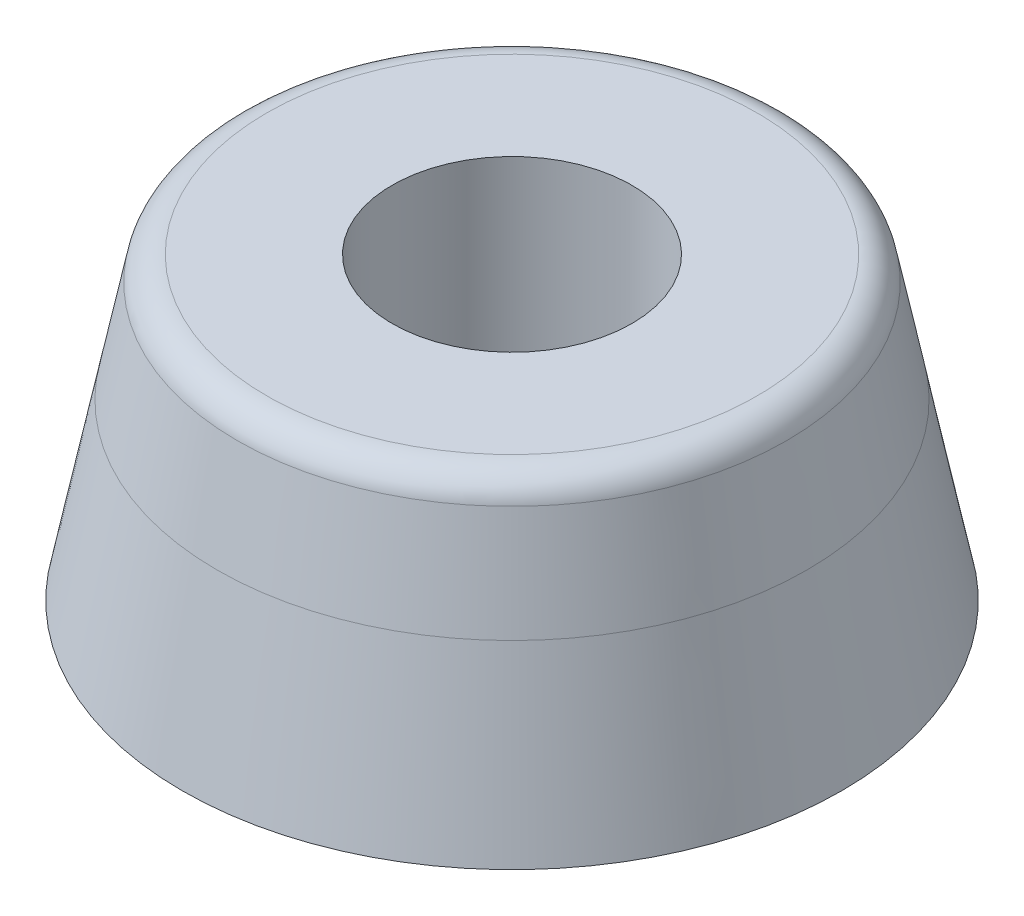
SolidWorks part; units mm, degrees
ref_plane "前视基准面" through (0, 0, 0) normal (0, 0, 1) x (1, 0, 0)
ref_plane "上视基准面" through (0, 0, 0) normal (0, 1, 0) x (1, 0, 0)
ref_plane "右视基准面" through (0, 0, 0) normal (1, 0, 0) x (0, 0, -1)
sketch "草图6" plane through (0, 0, 0) normal (0, 0, 1) x (1, 0, 0)
  line L0 (1.65, 0) -> (1.65, 4)
  line L1 (4, 10) -> (9, 10)
  line L2 (9, 10) -> (11, 0)
  line L3 (11, 0) -> (1.65, 0)
  line L4 (4, 10) -> (4, 4)
  line L5 (4, 4) -> (1.65, 4)
  line L6 (0, 0) -> (0, 13.1092) construction
  dimension "D1" = 22
  dimension "D2" = 18
  dimension "D3" = 10
  dimension "D4" = 3.3
  dimension "D5" = 8
  dimension "D6" = 4
revolve "旋转1" add sketch "草图6" angle 360 about L6
fillet "圆角1" radius 1 1 edges at (9, 10, 0)
sketch "草图7" plane through (0, 0, 0) normal (0, 0, 1) x (1, 0, 0)
  line L0 (-10.6027, 5.8) -> (11.6052, 5.8)
  dimension "D1" = 5.8
split line "分割线1"
